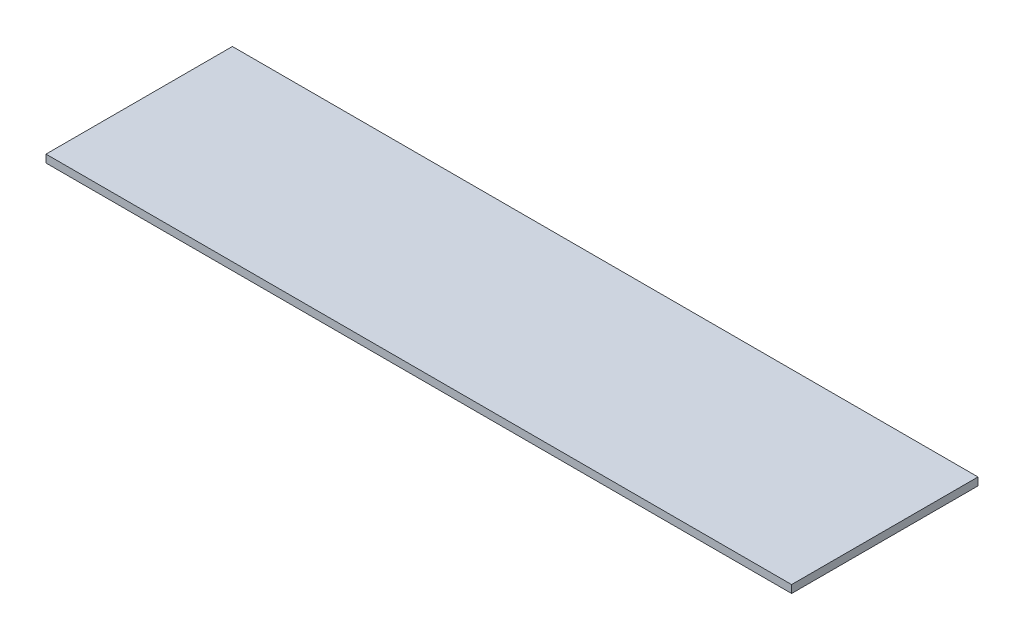
SolidWorks part; units mm, degrees
material "Acrylic (Medium-high impact)"
ref_plane "Front Plane" through (0, 0, 0) normal (0, 0, 1) x (1, 0, 0)
ref_plane "Top Plane" through (0, 0, 0) normal (0, 1, 0) x (1, 0, 0)
ref_plane "Right Plane" through (0, 0, 0) normal (1, 0, 0) x (0, 0, -1)
sketch "Sketch1" plane through (0, 0, 0) normal (0, 1, 0) x (1, 0, 0)
  line L1 (-304.8, -76.2) -> (304.8, -76.2)
  line L2 (-304.8, -76.2) -> (-304.8, 76.2)
  line L3 (-304.8, 76.2) -> (304.8, 76.2)
  line L4 (304.8, -76.2) -> (304.8, 76.2)
  line L5 (-304.8, -76.2) -> (304.8, 76.2) construction
  line L6 (-304.8, 76.2) -> (304.8, -76.2) construction
  point P0 (0, 0)
  dimension "D1" = 609.6
  dimension "D2" = 152.4
extrude "Boss-Extrude1" add sketch "Sketch1" along normal mid plane 6.35
